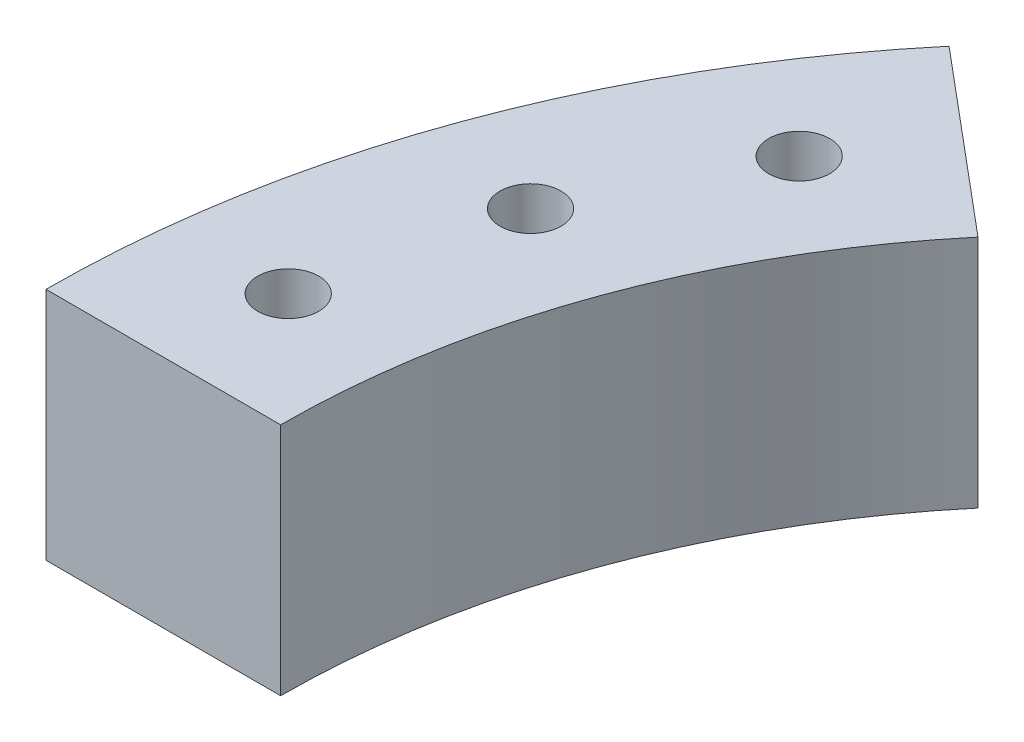
SolidWorks part; units mm, degrees
material "Custom Plastic"
ref_plane "Front Plane" through (0, 0, 0) normal (0, 0, 1) x (1, 0, 0)
ref_plane "Top Plane" through (0, 0, 0) normal (0, 1, 0) x (1, 0, 0)
ref_plane "Right Plane" through (0, 0, 0) normal (1, 0, 0) x (0, 0, -1)
sketch "Sketch1" plane through (0, 0, 0) normal (0, 1, 0) x (1, 0, 0)
  line L0 (0, 0) -> (65.2704, 0) construction
  line L1 (65.2704, 0) -> (65.2704, 50) construction
  line L2 (0, 0) -> (0, -10) construction
  line L3 (18.1985, 50) -> (-23.7565, 0) construction
  line L4 (10, 0) -> (-10, 0)
  line L5 (25.859, 43.5721) -> (10.5381, 56.4279)
  arc A0 (0, 0) -> (18.1985, 50) centre (77.7862, 0) cw construction
  arc A1 (10, 0) -> (25.859, 43.5721) centre (77.7862, 0) cw
  arc A2 (-10, 0) -> (10.5381, 56.4279) centre (77.7862, 0) cw
  circle A3 centre (0.6455, 10) radius 2.6
  circle A4 centre (4.6911, 26.6044) radius 2.6
  circle A5 centre (12.2651, 41.9247) radius 2.6
  circle A7 centre (23.0019, 55.2211) radius 2.6 [skipped]
  point P24 (77.7862, 0)
  dimension "D6" = 5.2
  dimension "D9" = 10
  dimension "D1" = 10
  dimension "D2" = 50
  dimension "D3" = 50
  dimension "D7" = 10
  dimension "D8" = 4
  dimension "D4" = 10
  dimension "D5" = 10
extrude "Boss-Extrude1" add sketch "Sketch1" along normal blind 20
